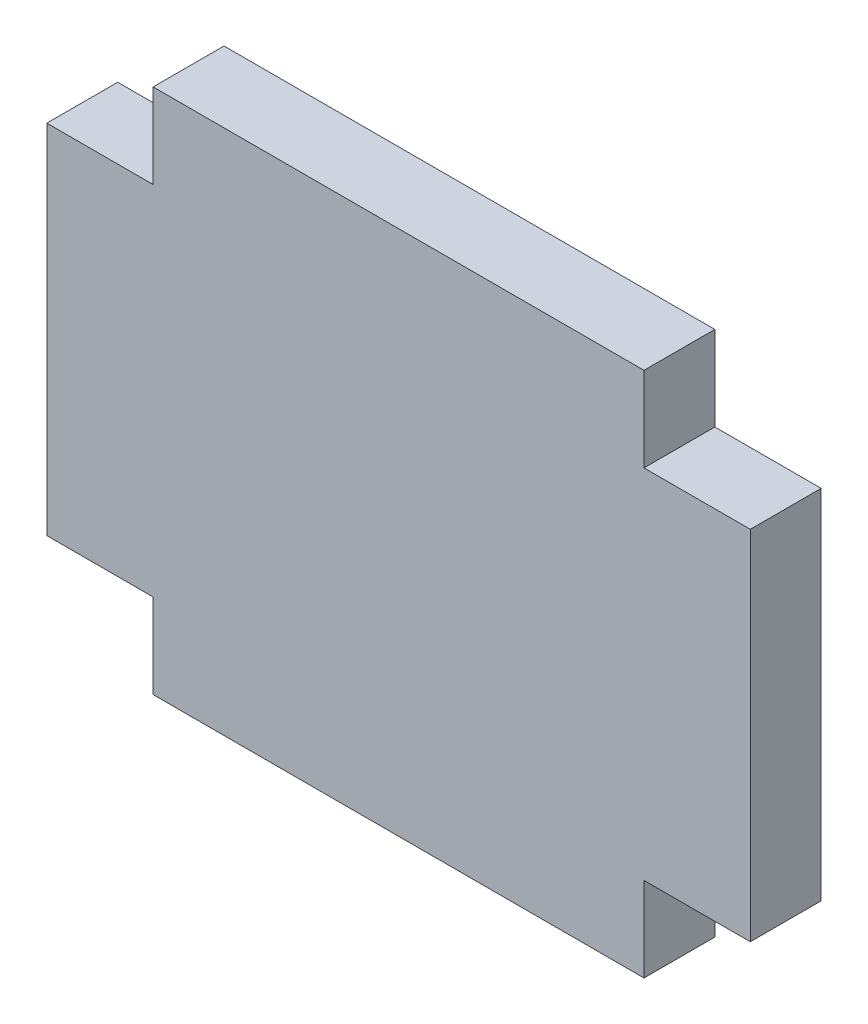
SolidWorks part; units mm, degrees
ref_plane "前视基准面" through (0, 0, 0) normal (0, 0, 1) x (1, 0, 0)
ref_plane "上视基准面" through (0, 0, 0) normal (0, 1, 0) x (1, 0, 0)
ref_plane "右视基准面" through (0, 0, 0) normal (1, 0, 0) x (0, 0, -1)
sketch "草图1" plane through (0, 0, 0) normal (0, 0, 1) x (1, 0, 0)
  line L24 (58.2631, -8.6584) -> (52.2631, -8.6584)
  line L25 (52.2631, -8.6584) -> (52.2631, -3.8884)
  line L26 (52.2631, -3.8884) -> (24.5631, -3.8884)
  line L27 (24.5631, -3.8884) -> (24.5631, -8.6584)
  line L28 (24.5631, -8.6584) -> (18.5631, -8.6584)
  line L29 (18.5631, -8.6584) -> (18.5631, -28.8184)
  line L30 (18.5631, -28.8184) -> (24.5631, -28.8184)
  line L31 (24.5631, -28.8184) -> (24.5631, -33.5884)
  line L32 (24.5631, -33.5884) -> (52.2631, -33.5884)
  line L33 (52.2631, -33.5884) -> (52.2631, -28.8184)
  line L34 (52.2631, -28.8184) -> (58.2631, -28.8184)
  line L35 (58.2631, -28.8184) -> (58.2631, -8.6584)
  line L36 (58.2631, -8.6584) -> (52.2631, -8.6584)
  line L37 (52.2631, -8.6584) -> (52.2631, -3.8884)
  line L38 (52.2631, -3.8884) -> (24.5631, -3.8884)
  line L39 (24.5631, -3.8884) -> (24.5631, -8.6584)
  line L40 (24.5631, -8.6584) -> (18.5631, -8.6584)
  line L41 (18.5631, -8.6584) -> (18.5631, -28.8184)
  line L42 (18.5631, -28.8184) -> (24.5631, -28.8184)
  line L43 (24.5631, -28.8184) -> (24.5631, -33.5884)
  line L44 (24.5631, -33.5884) -> (52.2631, -33.5884)
  line L45 (52.2631, -33.5884) -> (52.2631, -28.8184)
  line L46 (52.2631, -28.8184) -> (58.2631, -28.8184)
  line L47 (58.2631, -28.8184) -> (58.2631, -8.6584)
  dimension "D1" = 0.15
extrude "凸台-拉伸1" add sketch "草图1" along normal blind 4
